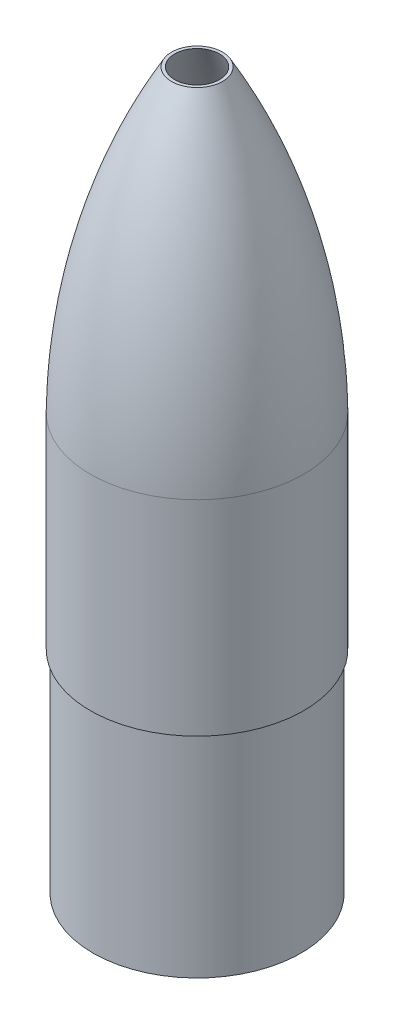
SolidWorks part; units mm, degrees
other "Markup1"
sketch "Sketch4" plane through (78.16, -154.2442, 78.16) normal (0.9651, -0.1718, 0.1975) x (-0.1686, -0.9851, -0.0334)
material "Thornel Mat VMA"
ref_plane "Front Plane" through (0, 0, 0) normal (0, 0, 1) x (1, 0, 0)
ref_plane "Top Plane" through (0, 0, 0) normal (0, 1, 0) x (1, 0, 0)
ref_plane "Right Plane" through (0, 0, 0) normal (1, 0, 0) x (0, 0, -1)
sketch "Sketch1" plane through (0, 0, 0) normal (0, 0, 1) x (1, 0, 0)
  line L0 (78.16, 0.5558) -> (78.16, 150.5558)
  line L3 (0, 0) -> (0, 614.1078) construction
  line L6 (0, -198.8179) -> (0, -350.074)
  line L7 (76.2, 0.5558) -> (76.2, 150.5443)
  line L8 (78.16, 0.5558) -> (76.2, 0.5558)
  line L9 (0, 400) -> (0, 396.4892)
  spline S0 degree 4 poles (-15.3468, 421.2955) (-15.0103, 420.856) (-14.3388, 419.9758) (-13.3353, 418.6515) (-12.0074, 416.8814) (-10.6914, 415.1091) (-9.395, 413.3458) (-8.1033, 411.5702) (-6.8448, 409.8242) (-5.5578, 408.0177) (-4.3521, 406.3128) (-3.0104, 404.3884) (-1.9663, 402.8848) (-0.427, 400.6308) (0.2737, 399.5978) (1.5381, 397.7184) (2.5222, 396.2406) (3.5056, 394.7509) (4.501, 393.2308) (5.4828, 391.7179) (6.46, 390.199) (7.4365, 388.6679) (8.4121, 387.1246) (16.4914, 374.2288) (28.348, 353.3444) (42.5411, 323.7528) (57.5292, 282.9984) (68.4498, 242.8729) (74.1096, 210.0768) (76.6559, 184.8086) (77.5185, 170.0675) (77.6804, 166.8514) (77.8002, 164.1053) (77.872, 162.2907) (77.9363, 160.4857) (77.9934, 158.6832) (78.0434, 156.8667) (78.0859, 155.0826) (78.1211, 153.3065) (78.1553, 151.0401) (78.1694, 149.7893) (78.1915, 147.0488) (78.1921, 145.2128) (78.1883, 142.8552) (78.1709, 140.7595) (78.1445, 138.5315) (78.1069, 136.371) (78.059, 134.1662) (78, 131.9694) (77.93, 129.7536) (77.8488, 127.533) (77.7798, 125.8658) (77.7301, 124.7552) (77.7044, 124.2) knots 0 0 0 0 0 0.006969 0.013937 0.020906 0.027875 0.034717 0.04156 0.048403 0.055246 0.062088 0.068931 0.075774 0.082616 0.0883 0.093983 0.099666 0.10535 0.111033 0.116716 0.122399 0.128083 0.133891 0.1397 0.313954 0.430124 0.546294 0.685698 0.836718 0.848335 0.865761 0.871569 0.877253 0.882936 0.888619 0.894302 0.899986 0.905669 0.911352 0.917035 0.923907 0.930779 0.93765 0.944522 0.951393 0.958265 0.965136 0.972008 0.979006 0.986004 0.993002 1 1 1 1 1 construction
  spline S1 degree 4 poles (0, 400) (0.2113, 399.6881) (0.6358, 399.0596) (1.5381, 397.7184) (2.5222, 396.2406) (3.5056, 394.7509) (4.501, 393.2308) (5.4828, 391.7179) (6.46, 390.199) (7.4365, 388.6679) (8.4121, 387.1246) (16.4914, 374.2288) (28.348, 353.3444) (42.5411, 323.7528) (57.5292, 282.9984) (68.4498, 242.8729) (74.1096, 210.0768) (76.6559, 184.8086) (77.5185, 170.0675) (77.6804, 166.8514) (77.8002, 164.1053) (77.872, 162.2907) (77.9363, 160.4857) (77.9934, 158.6832) (78.0434, 156.8667) (78.0859, 155.0826) (78.1211, 153.3065) (78.1455, 151.6911) (78.1556, 150.9325) (78.16, 150.5558) knots 0.082616 0.082616 0.082616 0.082616 0.082616 0.0883 0.093983 0.099666 0.10535 0.111033 0.116716 0.122399 0.128083 0.133891 0.1397 0.313954 0.430124 0.546294 0.685698 0.836718 0.848335 0.865761 0.871569 0.877253 0.882936 0.888619 0.894302 0.899986 0.905669 0.911352 0.917035 0.917035 0.917035 0.917035 0.917035
  spline S2 degree 1 poles (-1.6226, 398.9005) (76.2, 150.5443) knots 0 0 1 1 construction
  spline S3 degree 3 poles (-1.6226, 398.9005) (-1.4527, 398.6498) (-1.1386, 398.1849) (-0.5196, 397.2651) (0.1099, 396.3257) (0.6873, 395.459) (1.2483, 394.6123) (1.9995, 393.4729) (3.323, 391.4513) (5.1827, 388.5671) (9.5921, 381.5907) (18.7945, 366.2671) (36.7943, 332.2032) (57.0765, 280.9241) (69.6847, 227.2404) (74.343, 188.9958) (75.531, 171.161) (75.8913, 162.9157) (76.0101, 159.4861) (76.0769, 157.0706) (76.1102, 155.7062) (76.1328, 154.6907) (76.1533, 153.65) (76.1724, 152.5206) (76.189, 151.4097) (76.1964, 150.8476) (76.2, 150.5443) knots 0.082616 0.082616 0.082616 0.082616 0.085876 0.089135 0.092394 0.095654 0.098913 0.102172 0.108691 0.121728 0.134765 0.186913 0.29121 0.499804 0.708398 0.812695 0.864843 0.877881 0.890918 0.897436 0.900696 0.903955 0.907214 0.910473 0.913733 0.916992 0.916992 0.916992 0.916992 only from (0, 396.4892) to (76.2, 150.5443)
  point P11 (0, 400)
  dimension "D1" = 400
  dimension "D2" = 150
  dimension "D3" = 1.96
  dimension "D4" = 76.2
revolve "Revolve3" add sketch "Sketch1" angle 360 about L6
ref_plane "Plane1" through (0, 150.5558, 0) normal (0, 1, 0) x (1, 0, 0)
sketch "Sketch2" plane through (0, 150.5558, 0) normal (0, 1, 0) x (1, 0, 0)
  circle A0 centre (0, 0) radius 76.2 construction
  circle A1 centre (0, 0) radius 76.2
  circle A2 centre (0, 0) radius 73.2
  dimension "D1" = 3
extrude "Boss-Extrude1" add sketch "Sketch2" against normal blind 304.8
ref_plane "Plane2" through (0, 400, 0) normal (0, -1, 0) x (-1, 0, 0)
sketch "Sketch3" plane through (0, 400, 0) normal (0, -1, 0) x (-1, 0, 0)
  circle A0 centre (0, 0) radius 126.4604
extrude "Cut-Extrude1" cut sketch "Sketch3" along normal blind 30 contours A0
ref_plane "Plane3" through (0, -8.2442, 0) normal (0, -1, 0) x (-1, 0, 0)
sketch "Sketch5" plane through (0, -8.2442, 0) normal (0, -1, 0) x (-1, 0, 0)
  circle A0 centre (0, 0) radius 73.2
  circle A1 centre (0, 0) radius 73.2
